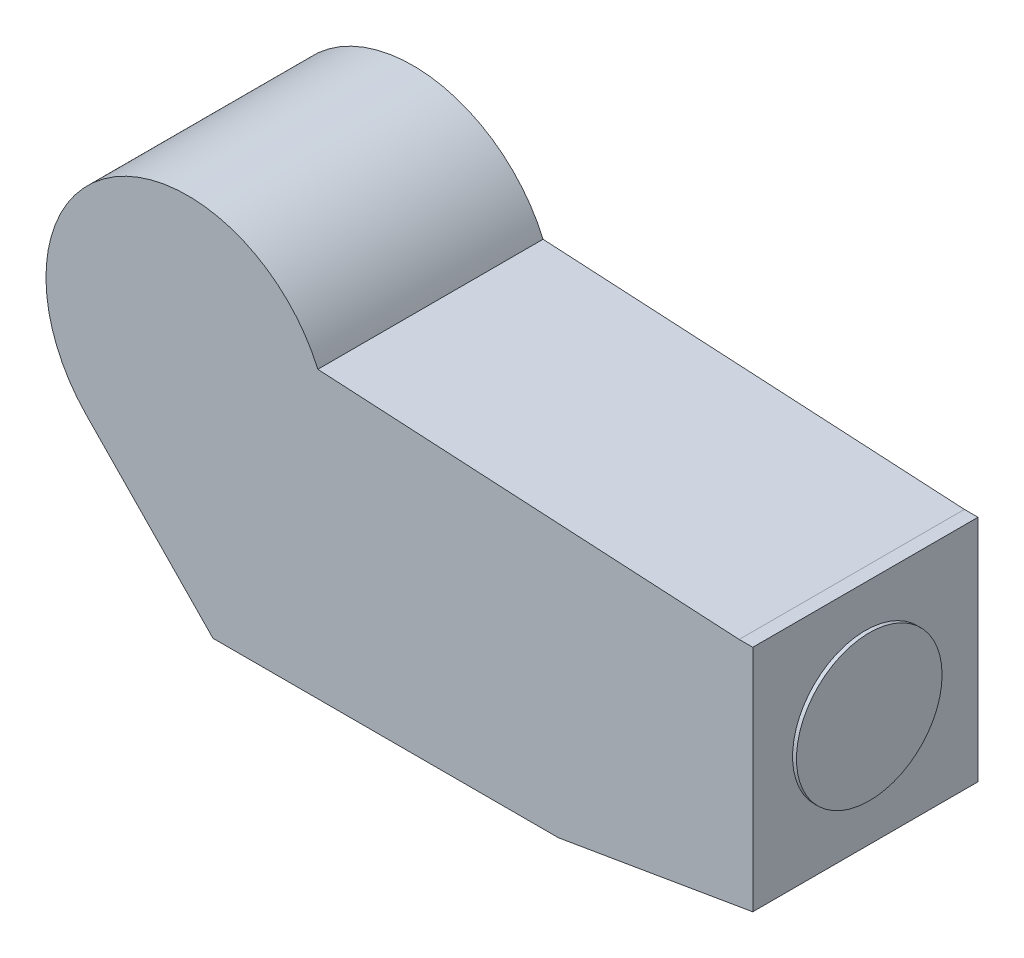
SolidWorks part; units mm, degrees
ref_plane "Front Plane" through (0, 0, 0) normal (0, 0, 1) x (1, 0, 0)
ref_plane "Top Plane" through (0, 0, 0) normal (0, 1, 0) x (1, 0, 0)
ref_plane "Right Plane" through (0, 0, 0) normal (1, 0, 0) x (0, 0, -1)
sketch "Sketch1" plane through (0, 0, 0) normal (0, 0, 1) x (1, 0, 0)
  line L0 (67, 28.9828) -> (284, 17)
  line L1 (284, 17) -> (291, 17)
  line L2 (291, 17) -> (291, -101)
  line L3 (291, -101) -> (191, -118)
  line L4 (191, -118) -> (13, -118)
  line L5 (13, -118) -> (-52.3049, -50.9234)
  line L6 (0, 0) -> (355.1665, 0) construction
  arc A0 (67, 28.9828) -> (-52.3049, -50.9234) centre (0, 0) ccw
  dimension "D1" = 146
  dimension "D3" = 291
  dimension "D4" = 178
  dimension "D5" = 100
  dimension "D6" = 17
  dimension "D7" = 101
  dimension "D8" = 118
  dimension "D9" = 7
extrude "Boss-Extrude1" add sketch "Sketch1" along normal mid plane 116
sketch "Sketch2" plane through (291, 0, 0) normal (1, 0, 0) x (0, 0, -1)
  circle A0 centre (0, -42) radius 37.5
extrude "Boss-Extrude2" add sketch "Sketch2" along normal blind 2
